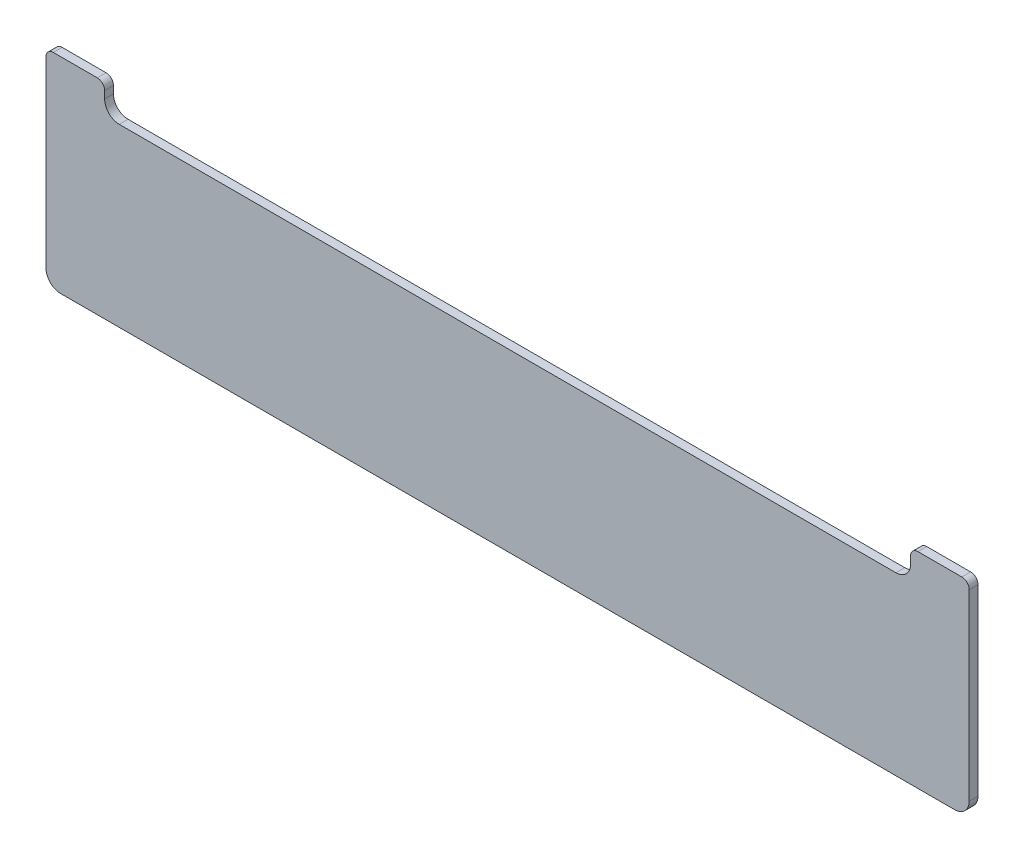
SolidWorks part; units mm, degrees
material "PC Alta viscosidad"
ref_plane "Alzado" through (0, 0, 0) normal (0, 0, 1) x (1, 0, 0)
ref_plane "Planta" through (0, 0, 0) normal (0, 1, 0) x (1, 0, 0)
ref_plane "Vista lateral" through (0, 0, 0) normal (1, 0, 0) x (0, 0, -1)
sketch "Sketch1" plane through (0, 0, 0) normal (0, 0, 1) x (1, 0, 0)
  line L1 (-157.5, -35) -> (157.5, -35)
  line L2 (-157.5, -35) -> (-157.5, 35)
  line L3 (-157.5, 35) -> (157.5, 35)
  line L4 (157.5, -35) -> (157.5, 35)
  line L5 (-157.5, -35) -> (157.5, 35) construction
  line L6 (-157.5, 35) -> (157.5, -35) construction
  point P0 (0, 0)
  dimension "D1" = 315
  dimension "D2" = 70
extrude "Boss-Extrude1" add sketch "Sketch1" along normal blind 3
sketch "Sketch2" plane through (0, 0, 3) normal (0, 0, 1) x (1, 0, 0)
  line L0 (157.5, 35) -> (-157.5, 35) construction
  line L1 (-137.5, 35) -> (137.5, 35)
  line L2 (-137.5, 35) -> (-137.5, 25)
  line L3 (-137.5, 25) -> (137.5, 25)
  line L4 (137.5, 35) -> (137.5, 25)
  line L6 (157.5, -35) -> (157.5, 35) construction
  point P6 (0, 25)
  dimension "D1" = 10
  dimension "D2" = 20
extrude "Cut-Extrude1" cut sketch "Sketch2" against normal blind 3
fillet "Fillet1" radius 5 4 edges at (137.5, 25, 1.5) (-137.5, 25, 1.5) (157.5, -35, 1.5) (-157.5, -35, 1.5)
fillet "Fillet2" radius 2.5 4 edges at (137.5, 35, 1.5) (157.5, 35, 1.5) (-157.5, 35, 1.5) (-137.5, 35, 1.5)
